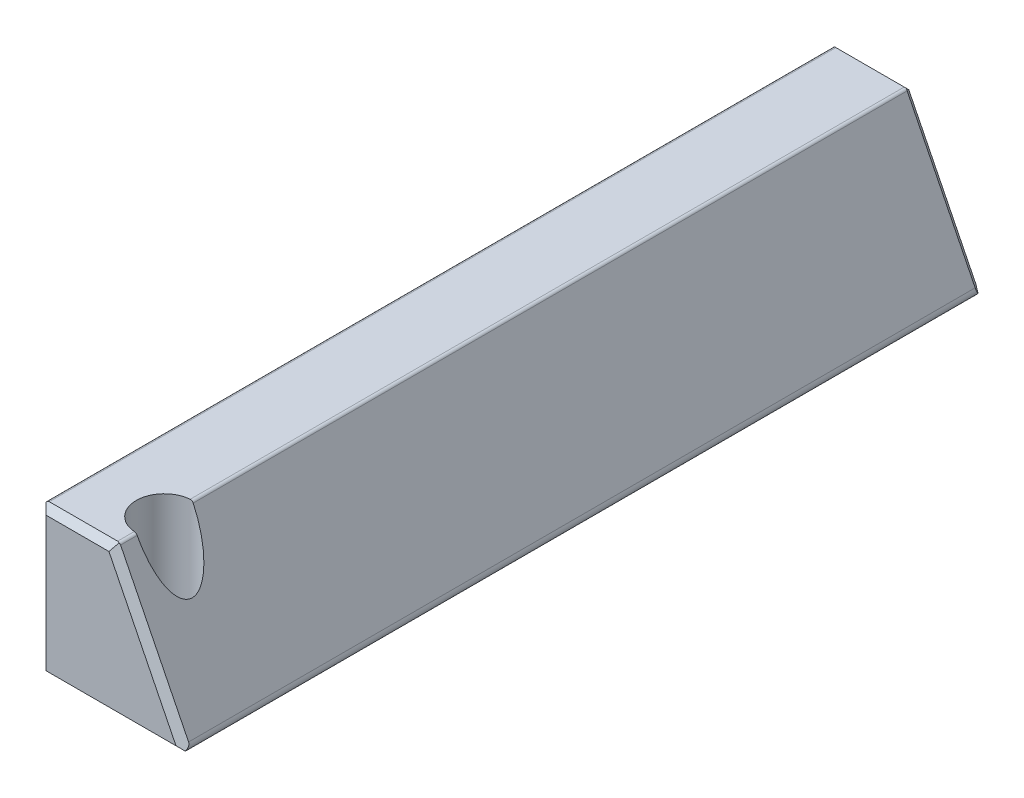
SolidWorks part; units mm, degrees
material "Chrome Stainless Steel"
ref_plane "Front Plane" through (0, 0, 0) normal (0, 0, 1) x (1, 0, 0)
ref_plane "Top Plane" through (0, 0, 0) normal (0, 1, 0) x (1, 0, 0)
ref_plane "Right Plane" through (0, 0, 0) normal (1, 0, 0) x (0, 0, -1)
sketch "Sketch1" plane through (0, 0, 0) normal (0, 0, 1) x (1, 0, 0)
  line L4 (0, 11.15) -> (0, 0)
  line L5 (0, 0) -> (11.1, 0)
  line L6 (11.1, 0) -> (5.55, 11.15)
  line L7 (5.55, 11.15) -> (0, 11.15)
  dimension "D1" = 11.15
  dimension "D2" = 11.1
  dimension "D3" = 5.55
extrude "Base" add sketch "Sketch1" along normal blind 60.25
chamfer "Face Chamfer" distance 0.5 angle 45 8 edges at (0, 5.575, 0) (5.55, 0, 0) (8.325, 5.575, 0) (2.775, 11.15, 0) (8.325, 5.575, 60.25) (5.55, 0, 60.25) (0, 5.575, 60.25) (2.775, 11.15, 60.25)
fillet "Smaller Fillets" radius 0.25 3 edges at (0, 0, 30.125) (0, 11.15, 30.125) (5.55, 11.15, 30.125)
fillet "Larger Fillet" radius 0.5 1 edges at (11.1, 0, 30.125)
sketch "Sketch2" plane through (0, 11.15, 0) normal (0, 1, 0) x (1, 0, 0)
  line L0 (5.55, -60.25) -> (5.55, 0) construction
  line L2 (5.55, -60.25) -> (0, -60.25) construction
  circle A1 centre (5.55, -56.39) radius 2.11
  dimension "D2" = 4.22
  dimension "D1" = 3.86
extrude "Hole" cut sketch "Sketch2" against normal through all
